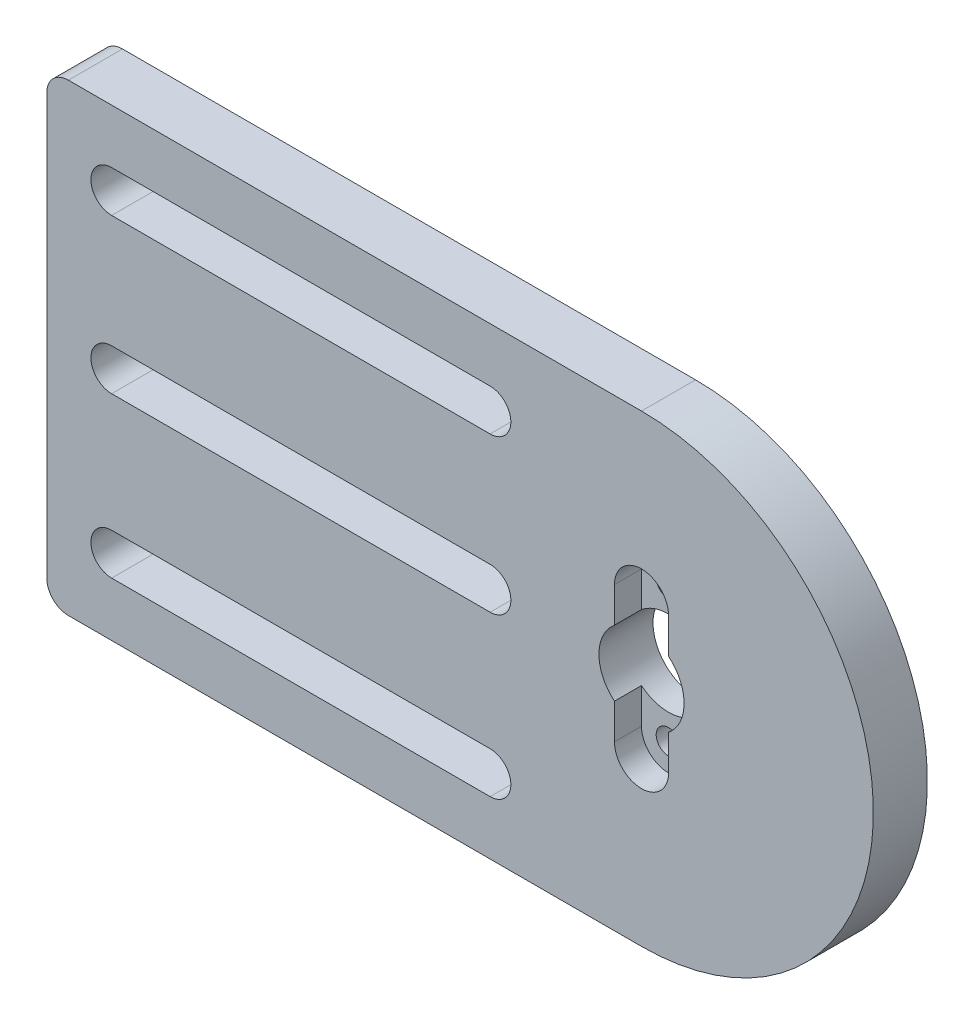
SolidWorks part; units mm, degrees
ref_plane "Front Plane" through (0, 0, 0) normal (0, 0, 1) x (1, 0, 0)
ref_plane "Top Plane" through (0, 0, 0) normal (0, 1, 0) x (1, 0, 0)
ref_plane "Right Plane" through (0, 0, 0) normal (1, 0, 0) x (0, 0, -1)
sketch "Sketch1" plane through (0, 0, 0) normal (0, 0, 1) x (1, 0, 0)
  line L0 (-4.497, -27.627) -> (-4.497, 26.8289)
  line L1 (65.353, 7.601) -> (65.353, -8.399) construction
  line L13 (47.573, 18.0439) -> (3.123, 18.0439) construction
  line L14 (47.573, 15.6089) -> (3.123, 15.6089)
  line L15 (65.353, 26.8289) -> (-4.497, 26.8289)
  line L17 (65.353, -27.627) -> (-4.497, -27.627)
  line L18 (47.573, 20.4789) -> (3.123, 20.4789)
  line L19 (3.123, -0.0862) -> (47.573, -0.0862) construction
  line L20 (3.123, 2.3488) -> (47.573, 2.3488)
  line L21 (3.123, -2.5212) -> (47.573, -2.5212)
  line L22 (3.123, -18.842) -> (47.573, -18.842) construction
  line L23 (3.123, -16.407) -> (47.573, -16.407)
  line L24 (3.123, -21.277) -> (47.573, -21.277)
  circle A0 centre (65.353, -0.399) radius 5
  circle A1 centre (65.353, -0.399) radius 8 construction
  circle A2 centre (65.353, 7.601) radius 1.45
  circle A3 centre (65.353, -8.399) radius 1.45
  arc A9 (65.353, -27.627) -> (65.353, 26.8289) centre (65.353, -0.399) ccw
  arc A14 (47.573, 15.6089) -> (47.573, 20.4789) centre (47.573, 18.0439) ccw
  arc A15 (3.123, 20.4789) -> (3.123, 15.6089) centre (3.123, 18.0439) ccw
  arc A19 (3.123, 2.3488) -> (3.123, -2.5212) centre (3.123, -0.0862) ccw
  arc A20 (47.573, -2.5212) -> (47.573, 2.3488) centre (47.573, -0.0862) ccw
  arc A21 (3.123, -16.407) -> (3.123, -21.277) centre (3.123, -18.842) ccw
  arc A22 (47.573, -21.277) -> (47.573, -16.407) centre (47.573, -18.842) ccw
  point P24 (-40.3376, 2.2383)
  point P49 (25.348, 18.0439)
  point P57 (25.348, -0.0862)
  point P62 (25.348, -18.842)
  dimension "D2" = 7.62
  dimension "D3" = 2.435
  dimension "D4" = 10
  dimension "D5" = 16
  dimension "D6" = 2.9
  dimension "D9" = 44.45
  dimension "D1" = 69.85
  dimension "D7" = 6.35
  dimension "D8" = 6.35
extrude "Boss-Extrude1" add sketch "Sketch1" along normal blind 6.35
fillet "Fillet1" radius 2.54 1 edges at (-4.497, -27.627, 3.175)
fillet "Fillet2" radius 2.54 1 edges at (-4.497, 26.8289, 3.175)
sketch "Sketch2" plane through (0, 0, 6.35) normal (0, 0, 1) x (1, 0, 0)
  line L0 (68.528, 7.601) -> (68.528, -8.399)
  line L2 (62.178, 7.601) -> (62.178, -8.399)
  arc A0 (68.528, 7.601) -> (62.178, 7.601) centre (65.353, 7.601) ccw
  arc A1 (62.178, -8.399) -> (68.528, -8.399) centre (65.353, -8.399) ccw
  dimension "D1" = 6.35
  dimension "D2" = 6.35
extrude "Cut-Extrude1" cut sketch "Sketch2" against normal blind 3.175
